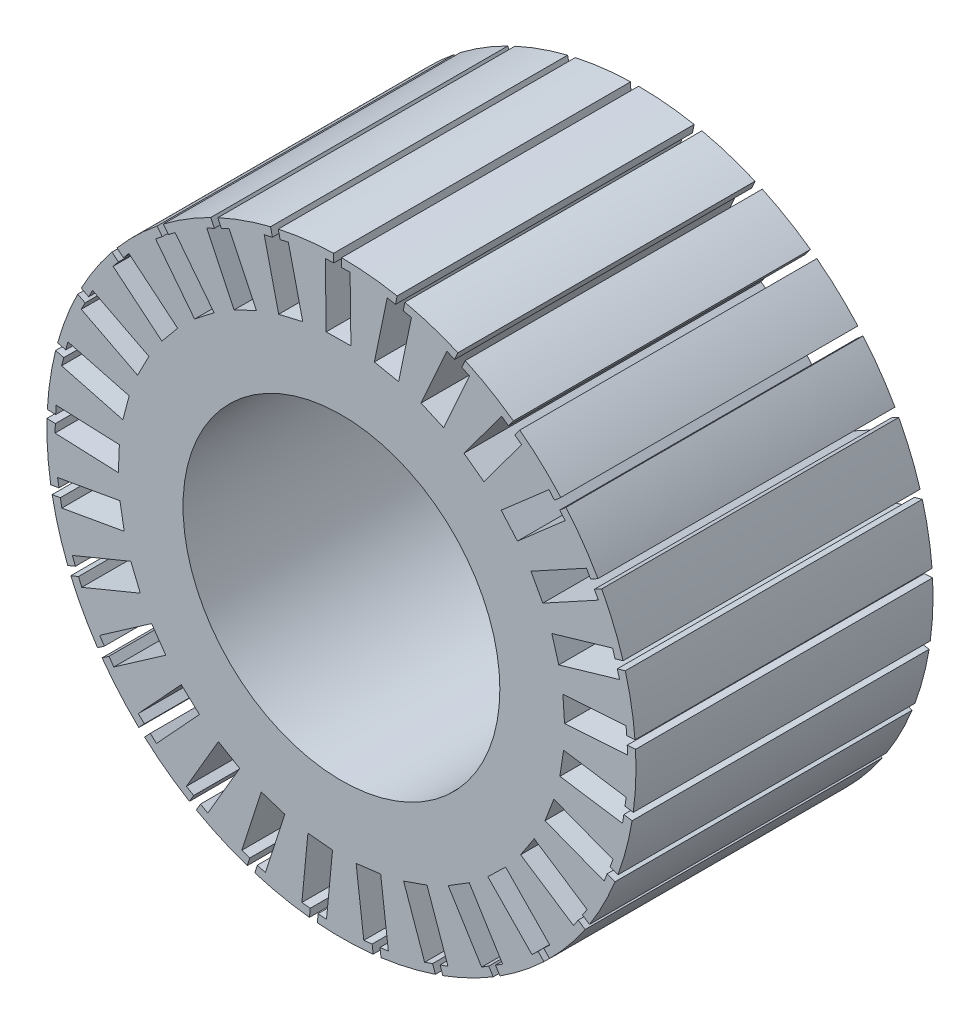
SolidWorks part; units mm, degrees
ref_plane "Спереди" through (0, 0, 0) normal (0, 0, 1) x (1, 0, 0)
ref_plane "Сверху" through (0, 0, 0) normal (0, 1, 0) x (1, 0, 0)
ref_plane "Справа" through (0, 0, 0) normal (1, 0, 0) x (0, 0, -1)
sketch "Эскиз1" plane through (0, 0, 0) normal (0, 0, 1) x (1, 0, 0)
  circle A0 centre (0, 0) radius 29.75
  circle A1 centre (0, 0) radius 16
extrude "Rotor_stack" add sketch "Эскиз1" along normal blind 30 from offset 15
sketch "Эскиз2" plane through (0, 0, 0) normal (0, 0, 1) x (1, 0, 0)
  line L0 (30.7049, 1.6645) -> (28.8617, 1.5405)
  line L1 (28.8617, 1.5405) -> (28.9187, 0.6924)
  line L2 (28.9187, 0.6924) -> (22.5332, 0.2629)
  line L3 (22.5332, 0.2629) -> (22.3654, 2.7573)
  line L4 (22.3654, 2.7573) -> (28.7509, 3.1868)
  line L5 (28.7509, 3.1868) -> (28.808, 2.3387)
  line L6 (28.808, 2.3387) -> (30.6512, 2.4627)
  line L7 (30.6512, 2.4627) -> (30.7049, 1.6645)
  line L8 (29.6292, 8.2262) -> (27.8557, 7.7089)
  line L9 (27.8557, 7.7089) -> (28.0938, 6.8929)
  line L10 (28.0938, 6.8929) -> (21.9498, 5.1007)
  line L11 (21.9498, 5.1007) -> (21.2498, 7.5007)
  line L12 (21.2498, 7.5007) -> (27.3937, 9.2929)
  line L13 (27.3937, 9.2929) -> (27.6317, 8.4769)
  line L14 (27.6317, 8.4769) -> (29.4052, 8.9942)
  line L15 (29.4052, 8.9942) -> (29.6292, 8.2262)
  line L16 (27.1681, 14.4033) -> (25.5473, 13.5168)
  line L17 (25.5473, 13.5168) -> (25.9552, 12.7711)
  line L18 (25.9552, 12.7711) -> (20.3402, 9.7)
  line L19 (20.3402, 9.7) -> (19.1405, 11.8934)
  line L20 (19.1405, 11.8934) -> (24.7556, 14.9645)
  line L21 (24.7556, 14.9645) -> (25.1634, 14.2187)
  line L22 (25.1634, 14.2187) -> (26.7842, 15.1052)
  line L23 (26.7842, 15.1052) -> (27.1681, 14.4033)
  line L24 (23.4367, 19.9069) -> (22.0443, 18.6927)
  line L25 (22.0443, 18.6927) -> (22.603, 18.0521)
  line L26 (22.603, 18.0521) -> (17.7794, 13.8458)
  line L27 (17.7794, 13.8458) -> (16.1363, 15.73)
  line L28 (16.1363, 15.73) -> (20.9599, 19.9363)
  line L29 (20.9599, 19.9363) -> (21.5185, 19.2957)
  line L30 (21.5185, 19.2957) -> (22.9109, 20.5099)
  line L31 (22.9109, 20.5099) -> (23.4367, 19.9069)
  line L32 (18.6093, 24.4797) -> (17.5105, 22.9946)
  line L33 (17.5105, 22.9946) -> (18.1938, 22.489)
  line L34 (18.1938, 22.489) -> (14.3873, 17.3441)
  line L35 (14.3873, 17.3441) -> (12.3776, 18.8311)
  line L36 (12.3776, 18.8311) -> (16.1841, 23.976)
  line L37 (16.1841, 23.976) -> (16.8674, 23.4704)
  line L38 (16.8674, 23.4704) -> (17.9662, 24.9555)
  line L39 (17.9662, 24.9555) -> (18.6093, 24.4797)
  line L40 (12.9118, 27.9078) -> (12.158, 26.2212)
  line L41 (12.158, 26.2212) -> (12.934, 25.8744)
  line L42 (12.934, 25.8744) -> (10.3225, 20.0315)
  line L43 (10.3225, 20.0315) -> (8.0401, 21.0516)
  line L44 (8.0401, 21.0516) -> (10.6516, 26.8945)
  line L45 (10.6516, 26.8945) -> (11.4276, 26.5477)
  line L46 (11.4276, 26.5477) -> (12.1815, 28.2343)
  line L47 (12.1815, 28.2343) -> (12.9118, 27.9078)
  line L48 (6.6106, 30.031) -> (6.237, 28.2218)
  line L49 (6.237, 28.2218) -> (7.0694, 28.0499)
  line L50 (7.0694, 28.0499) -> (5.7749, 21.7822)
  line L51 (5.7749, 21.7822) -> (3.3266, 22.2878)
  line L52 (3.3266, 22.2878) -> (4.6211, 28.5555)
  line L53 (4.6211, 28.5555) -> (5.4535, 28.3836)
  line L54 (5.4535, 28.3836) -> (5.8271, 30.1928)
  line L55 (5.8271, 30.1928) -> (6.6106, 30.031)
  line L56 (0.0003, 30.75) -> (0.0243, 28.9028)
  line L57 (0.0243, 28.9028) -> (0.8742, 28.9138)
  line L58 (0.8742, 28.9138) -> (0.9574, 22.5143)
  line L59 (0.9574, 22.5143) -> (-1.5424, 22.4818)
  line L60 (-1.5424, 22.4818) -> (-1.6256, 28.8813)
  line L61 (-1.6256, 28.8813) -> (-0.7756, 28.8924)
  line L62 (-0.7756, 28.8924) -> (-0.7997, 30.7396)
  line L63 (-0.7997, 30.7396) -> (0.0003, 30.75)
  line L64 (-6.6101, 30.0311) -> (-6.1895, 28.2322)
  line L65 (-6.1895, 28.2322) -> (-5.3618, 28.4257)
  line L66 (-5.3618, 28.4257) -> (-3.9049, 22.1938)
  line L67 (-3.9049, 22.1938) -> (-6.3393, 21.6247)
  line L68 (-6.3393, 21.6247) -> (-7.7962, 27.8566)
  line L69 (-7.7962, 27.8566) -> (-6.9685, 28.0501)
  line L70 (-6.9685, 28.0501) -> (-7.3891, 29.849)
  line L71 (-7.3891, 29.849) -> (-6.6101, 30.0311)
  line L72 (-12.9113, 27.9081) -> (-12.1139, 26.2416)
  line L73 (-12.1139, 26.2416) -> (-11.3472, 26.6085)
  line L74 (-11.3472, 26.6085) -> (-8.5846, 20.8355)
  line L75 (-8.5846, 20.8355) -> (-10.8397, 19.7563)
  line L76 (-10.8397, 19.7563) -> (-13.6023, 25.5294)
  line L77 (-13.6023, 25.5294) -> (-12.8355, 25.8963)
  line L78 (-12.8355, 25.8963) -> (-13.633, 27.5627)
  line L79 (-13.633, 27.5627) -> (-12.9113, 27.9081)
  line L80 (-18.6089, 24.48) -> (-17.4719, 23.024)
  line L81 (-17.4719, 23.024) -> (-16.8019, 23.5471)
  line L82 (-16.8019, 23.5471) -> (-12.8629, 18.5029)
  line L83 (-12.8629, 18.5029) -> (-14.8333, 16.9642)
  line L84 (-14.8333, 16.9642) -> (-18.7723, 22.0085)
  line L85 (-18.7723, 22.0085) -> (-18.1024, 22.5316)
  line L86 (-18.1024, 22.5316) -> (-19.2394, 23.9876)
  line L87 (-19.2394, 23.9876) -> (-18.6089, 24.48)
  line L88 (-23.4363, 19.9073) -> (-22.0129, 18.7298)
  line L89 (-22.0129, 18.7298) -> (-21.4711, 19.3847)
  line L90 (-21.4711, 19.3847) -> (-16.5398, 15.3052)
  line L91 (-16.5398, 15.3052) -> (-18.1333, 13.3789)
  line L92 (-18.1333, 13.3789) -> (-23.0646, 17.4584)
  line L93 (-23.0646, 17.4584) -> (-22.5228, 18.1133)
  line L94 (-22.5228, 18.1133) -> (-23.9462, 19.2909)
  line L95 (-23.9462, 19.2909) -> (-23.4363, 19.9073)
  line L96 (-27.1679, 14.4038) -> (-25.5246, 13.5598)
  line L97 (-25.5246, 13.5598) -> (-25.1362, 14.3158)
  line L98 (-25.1362, 14.3158) -> (-19.4432, 11.3918)
  line L99 (-19.4432, 11.3918) -> (-20.5854, 9.168)
  line L100 (-20.5854, 9.168) -> (-26.2784, 12.092)
  line L101 (-26.2784, 12.092) -> (-25.8901, 12.8481)
  line L102 (-25.8901, 12.8481) -> (-27.5334, 13.6922)
  line L103 (-27.5334, 13.6922) -> (-27.1679, 14.4038)
  line L104 (-29.6291, 8.2268) -> (-27.8428, 7.7557)
  line L105 (-27.8428, 7.7557) -> (-27.626, 8.5776)
  line L106 (-27.626, 8.5776) -> (-21.4376, 6.9457)
  line L107 (-21.4376, 6.9457) -> (-22.075, 4.5284)
  line L108 (-22.075, 4.5284) -> (-28.2635, 6.1602)
  line L109 (-28.2635, 6.1602) -> (-28.0467, 6.9822)
  line L110 (-28.0467, 6.9822) -> (-29.8331, 7.4532)
  line L111 (-29.8331, 7.4532) -> (-29.6291, 8.2268)
  line L112 (-30.7049, 1.665) -> (-28.8591, 1.589)
  line L113 (-28.8591, 1.589) -> (-28.8241, 2.4383)
  line L114 (-28.8241, 2.4383) -> (-22.4295, 2.1749)
  line L115 (-22.4295, 2.1749) -> (-22.5324, -0.323)
  line L116 (-22.5324, -0.323) -> (-28.927, -0.0596)
  line L117 (-28.927, -0.0596) -> (-28.892, 0.7897)
  line L118 (-28.892, 0.7897) -> (-30.7378, 0.8657)
  line L119 (-30.7378, 0.8657) -> (-30.7049, 1.665)
  line L120 (-30.345, -4.9745) -> (-28.5259, -4.652)
  line L121 (-28.5259, -4.652) -> (-28.6743, -3.815)
  line L122 (-28.6743, -3.815) -> (-22.3726, -2.6976)
  line L123 (-22.3726, -2.6976) -> (-21.9362, -5.1592)
  line L124 (-21.9362, -5.1592) -> (-28.2379, -6.2766)
  line L125 (-28.2379, -6.2766) -> (-28.3863, -5.4397)
  line L126 (-28.3863, -5.4397) -> (-30.2053, -5.7622)
  line L127 (-30.2053, -5.7622) -> (-30.345, -4.9745)
  line L128 (-28.5661, -11.3815) -> (-26.859, -10.6755)
  line L129 (-26.859, -10.6755) -> (-27.1838, -9.89)
  line L130 (-27.1838, -9.89) -> (-21.2697, -7.444)
  line L131 (-21.2697, -7.444) -> (-20.3142, -9.7542)
  line L132 (-20.3142, -9.7542) -> (-26.2284, -12.2002)
  line L133 (-26.2284, -12.2002) -> (-26.5532, -11.4147)
  line L134 (-26.5532, -11.4147) -> (-28.2604, -12.1208)
  line L135 (-28.2604, -12.1208) -> (-28.5661, -11.3815)
  line L136 (-25.4516, -17.2563) -> (-23.9361, -16.1998)
  line L137 (-23.9361, -16.1998) -> (-24.4222, -15.5025)
  line L138 (-24.4222, -15.5025) -> (-19.1722, -11.8423)
  line L139 (-19.1722, -11.8423) -> (-17.7424, -13.8931)
  line L140 (-17.7424, -13.8931) -> (-22.9925, -17.5533)
  line L141 (-22.9925, -17.5533) -> (-23.4786, -16.856)
  line L142 (-23.4786, -16.856) -> (-24.9941, -17.9125)
  line L143 (-24.9941, -17.9125) -> (-25.4516, -17.2563)
  line L144 (-21.147, -22.3242) -> (-19.894, -20.9666)
  line L145 (-19.894, -20.9666) -> (-20.5187, -20.3901)
  line L146 (-20.5187, -20.3901) -> (-16.1782, -15.6869)
  line L147 (-16.1782, -15.6869) -> (-14.341, -17.3824)
  line L148 (-14.341, -17.3824) -> (-18.6815, -22.0856)
  line L149 (-18.6815, -22.0856) -> (-19.3061, -21.5091)
  line L150 (-19.3061, -21.5091) -> (-20.5591, -22.8667)
  line L151 (-20.5591, -22.8667) -> (-21.147, -22.3242)
  line L152 (-15.8535, -26.3482) -> (-14.9217, -24.753)
  line L153 (-14.9217, -24.753) -> (-15.6557, -24.3243)
  line L154 (-15.6557, -24.3243) -> (-12.4277, -18.798)
  line L155 (-12.4277, -18.798) -> (-10.269, -20.0589)
  line L156 (-10.269, -20.0589) -> (-13.497, -25.5852)
  line L157 (-13.497, -25.5852) -> (-14.2309, -25.1565)
  line L158 (-14.2309, -25.1565) -> (-15.1627, -26.7517)
  line L159 (-15.1627, -26.7517) -> (-15.8535, -26.3482)
  line L160 (-9.8188, -29.1402) -> (-9.2517, -27.382)
  line L161 (-9.2517, -27.382) -> (-10.0607, -27.1211)
  line L162 (-10.0607, -27.1211) -> (-8.0962, -21.0301)
  line L163 (-8.0962, -21.0301) -> (-5.7168, -21.7975)
  line L164 (-5.7168, -21.7975) -> (-7.6814, -27.8885)
  line L165 (-7.6814, -27.8885) -> (-8.4903, -27.6276)
  line L166 (-8.4903, -27.6276) -> (-9.0574, -29.3858)
  line L167 (-9.0574, -29.3858) -> (-9.8188, -29.1402)
  line L168 (-3.3249, -30.5697) -> (-3.1491, -28.7307)
  line L169 (-3.1491, -28.7307) -> (-3.9952, -28.6498)
  line L170 (-3.9952, -28.6498) -> (-3.386, -22.2789)
  line L171 (-3.386, -22.2789) -> (-0.8974, -22.5168)
  line L172 (-0.8974, -22.5168) -> (-1.5066, -28.8878)
  line L173 (-1.5066, -28.8878) -> (-2.3527, -28.8069)
  line L174 (-2.3527, -28.8069) -> (-2.5286, -30.6459)
  line L175 (-2.5286, -30.6459) -> (-3.3249, -30.5697)
  line L176 (3.3244, -30.5698) -> (3.1008, -28.736)
  line L177 (3.1008, -28.736) -> (2.257, -28.8388)
  line L178 (2.257, -28.8388) -> (1.4824, -22.4859)
  line L179 (1.4824, -22.4859) -> (3.9641, -22.1833)
  line L180 (3.9641, -22.1833) -> (4.7387, -28.5362)
  line L181 (4.7387, -28.5362) -> (3.8949, -28.6391)
  line L182 (3.8949, -28.6391) -> (4.1185, -30.4729)
  line L183 (4.1185, -30.4729) -> (3.3244, -30.5698)
  line L184 (9.8183, -29.1404) -> (9.2057, -27.3975)
  line L185 (9.2057, -27.3975) -> (8.4038, -27.6794)
  line L186 (8.4038, -27.6794) -> (6.2816, -21.6415)
  line L187 (6.2816, -21.6415) -> (8.6401, -20.8125)
  line L188 (8.6401, -20.8125) -> (10.7623, -26.8504)
  line L189 (10.7623, -26.8504) -> (9.9604, -27.1323)
  line L190 (9.9604, -27.1323) -> (10.573, -28.8751)
  line L191 (10.573, -28.8751) -> (9.8183, -29.1404)
  line L192 (15.853, -26.3485) -> (14.8801, -24.7781)
  line L193 (14.8801, -24.7781) -> (14.1575, -25.2257)
  line L194 (14.1575, -25.2257) -> (10.787, -19.7852)
  line L195 (10.787, -19.7852) -> (12.9122, -18.4686)
  line L196 (12.9122, -18.4686) -> (16.2828, -23.9091)
  line L197 (16.2828, -23.9091) -> (15.5602, -24.3567)
  line L198 (15.5602, -24.3567) -> (16.5331, -25.9272)
  line L199 (16.5331, -25.9272) -> (15.853, -26.3485)
  line L200 (21.1466, -22.3245) -> (19.8588, -21)
  line L201 (19.8588, -21) -> (19.2493, -21.5925)
  line L202 (19.2493, -21.5925) -> (14.788, -17.0037)
  line L203 (14.788, -17.0037) -> (16.5805, -15.261)
  line L204 (16.5805, -15.261) -> (21.0418, -19.8498)
  line L205 (21.0418, -19.8498) -> (20.4324, -20.4423)
  line L206 (20.4324, -20.4423) -> (21.7202, -21.7669)
  line L207 (21.7202, -21.7669) -> (21.1466, -22.3245)
  line L208 (25.4513, -17.2567) -> (23.9089, -16.24)
  line L209 (23.9089, -16.24) -> (23.441, -16.9496)
  line L210 (23.441, -16.9496) -> (18.0976, -13.4272)
  line L211 (18.0976, -13.4272) -> (19.4735, -11.3399)
  line L212 (19.4735, -11.3399) -> (24.817, -14.8623)
  line L213 (24.817, -14.8623) -> (24.3492, -15.572)
  line L214 (24.3492, -15.572) -> (25.8916, -16.5888)
  line L215 (25.8916, -16.5888) -> (25.4513, -17.2567)
  line L216 (28.5659, -11.382) -> (26.841, -10.7206)
  line L217 (26.841, -10.7206) -> (26.5367, -11.5142)
  line L218 (26.5367, -11.5142) -> (20.5609, -9.2228)
  line L219 (20.5609, -9.2228) -> (21.456, -6.8886)
  line L220 (21.456, -6.8886) -> (27.4318, -9.18)
  line L221 (27.4318, -9.18) -> (27.1274, -9.9736)
  line L222 (27.1274, -9.9736) -> (28.8524, -10.635)
  line L223 (28.8524, -10.635) -> (28.5659, -11.382)
  line L224 (30.3449, -4.9751) -> (28.5181, -4.6999)
  line L225 (28.5181, -4.6999) -> (28.3915, -5.5404)
  line L226 (28.3915, -5.5404) -> (22.0629, -4.5872)
  line L227 (22.0629, -4.5872) -> (22.4352, -2.1151)
  line L228 (22.4352, -2.1151) -> (28.7638, -3.0683)
  line L229 (28.7638, -3.0683) -> (28.6372, -3.9088)
  line L230 (28.6372, -3.9088) -> (30.464, -4.184)
  line L231 (30.464, -4.184) -> (30.3449, -4.9751)
extrude "Rotor_slots" cut sketch "Эскиз2" against normal mid plane 32
